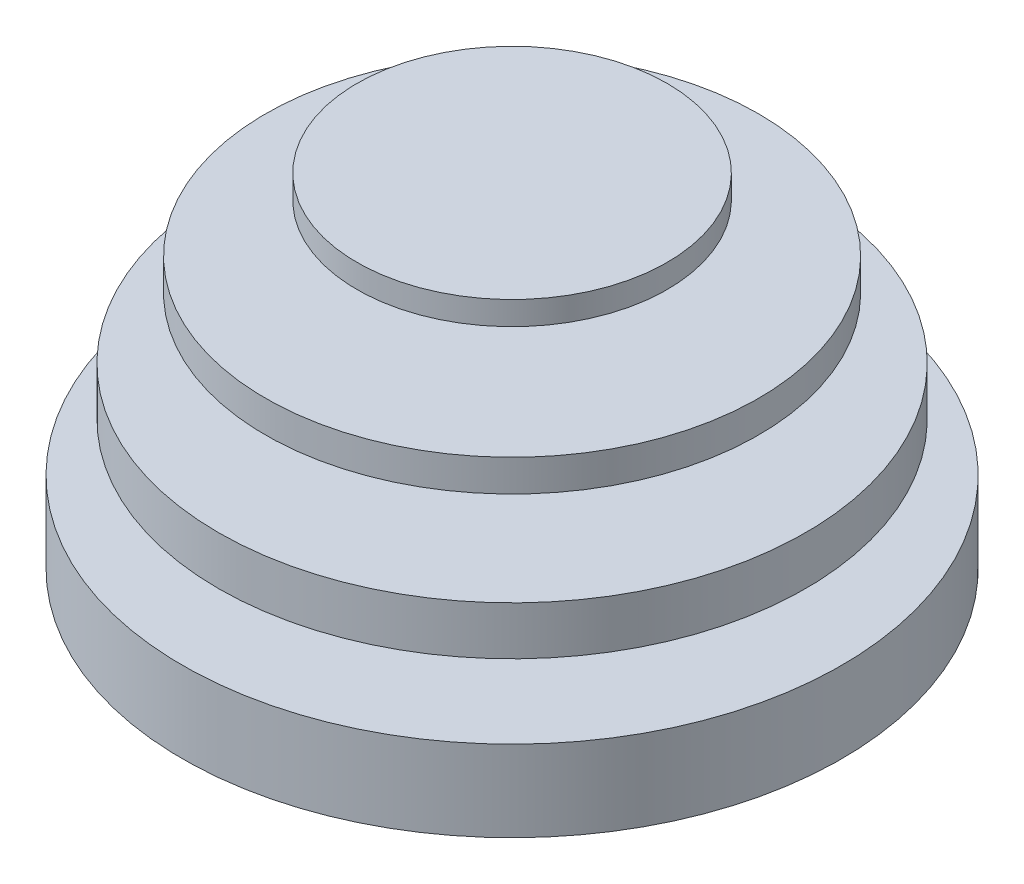
SolidWorks part; units mm, degrees
material "AISI 1020"
ref_plane "Front Plane" through (0, 0, 0) normal (0, 0, 1) x (1, 0, 0)
ref_plane "Top Plane" through (0, 0, 0) normal (0, 1, 0) x (1, 0, 0)
ref_plane "Right Plane" through (0, 0, 0) normal (1, 0, 0) x (0, 0, -1)
sketch "Sketch1" plane through (0, 0, 0) normal (0, 0, 1) x (1, 0, 0)
  line L1 (0, 0) -> (64.4987, 0)
  line L2 (0, 0) -> (0, 15.8537)
  line L3 (0, 15.8537) -> (64.4987, 15.8537)
  line L4 (64.4987, 0) -> (64.4987, 15.8537)
  line L5 (0, 25.3388) -> (57.4526, 25.3388)
  line L6 (0, 25.3388) -> (0, 34.8239)
  line L7 (0, 34.8239) -> (57.4526, 34.8239)
  line L8 (57.4526, 25.3388) -> (57.4526, 34.8239)
  line L9 (0, 46.748) -> (48.2385, 46.748)
  line L10 (0, 46.748) -> (0, 52.9811)
  line L11 (0, 52.9811) -> (48.2385, 52.9811)
  line L12 (48.2385, 46.748) -> (48.2385, 52.9811)
  line L13 (0, 62.4662) -> (30.3523, 62.4662)
  line L14 (0, 62.4662) -> (0, 67.0732)
  line L15 (0, 67.0732) -> (30.3523, 67.0732)
  line L16 (30.3523, 62.4662) -> (30.3523, 67.0732)
revolve "Revolve1" add sketch "Sketch1" angle 360 about L6
